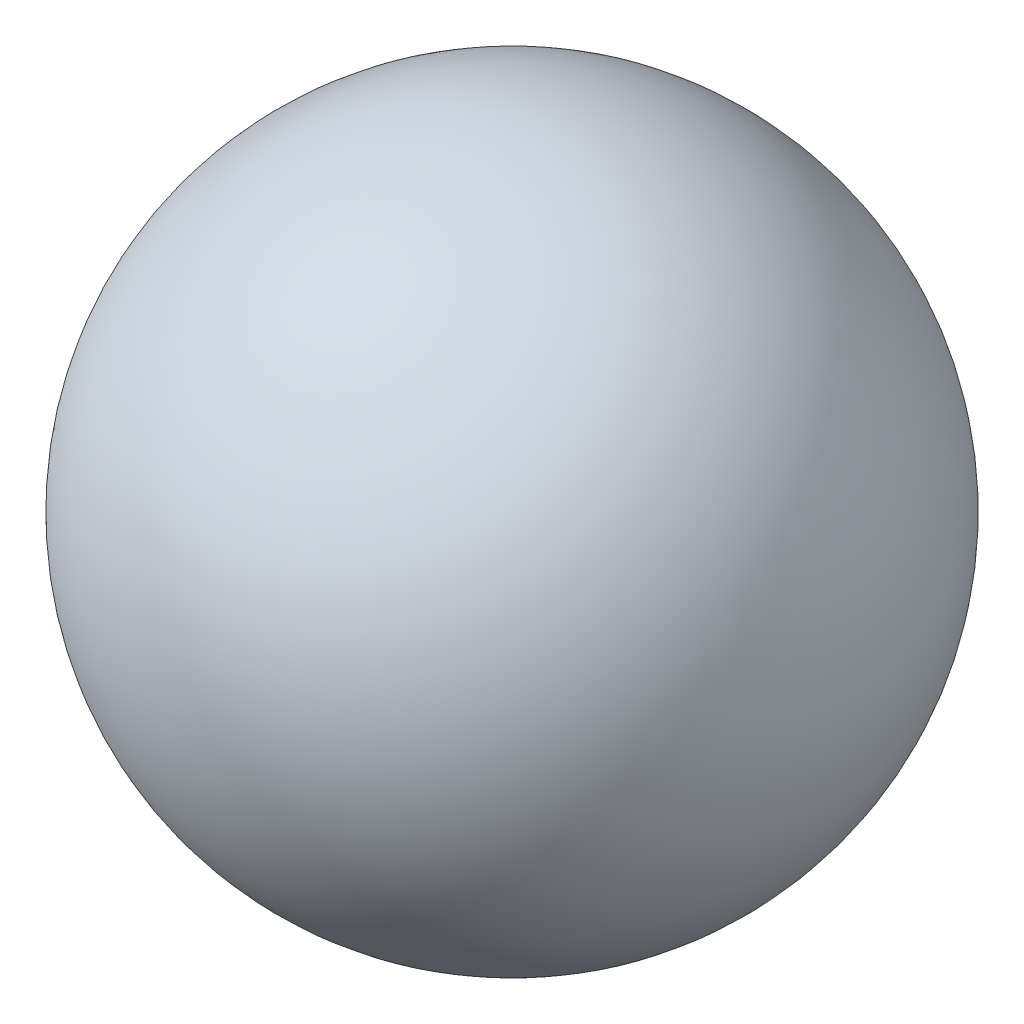
SolidWorks part; units mm, degrees
ref_plane "Front" through (0, 0, 0) normal (0, 0, 1) x (1, 0, 0)
ref_plane "Top" through (0, 0, 0) normal (0, 1, 0) x (1, 0, 0)
ref_plane "Right" through (0, 0, 0) normal (1, 0, 0) x (0, 0, -1)
sketch "Sketch1" plane through (0, 0, 0) normal (0, 0, 1) x (1, 0, 0)
  line L0 (0, 31.5) -> (0, -31.5) construction
  line L1 (0, 31.5) -> (0, -31.5)
  arc A0 (0, 31.5) -> (0, -31.5) centre (0, 0) cw
  point P1 (0, 0)
  point P2 (0.8031, -11.2102)
  dimension "D1" = 31.5
  dimension "D2" = 63
revolve "Revolve1" add sketch "Sketch1" angle 360 about L0
sketch "Sketch2" plane through (0, 0, 0) normal (0, 0, 1) x (1, 0, 0)
  circle A0 centre (0, 0) radius 31.5 construction
  point P0 (0, -31.5)
